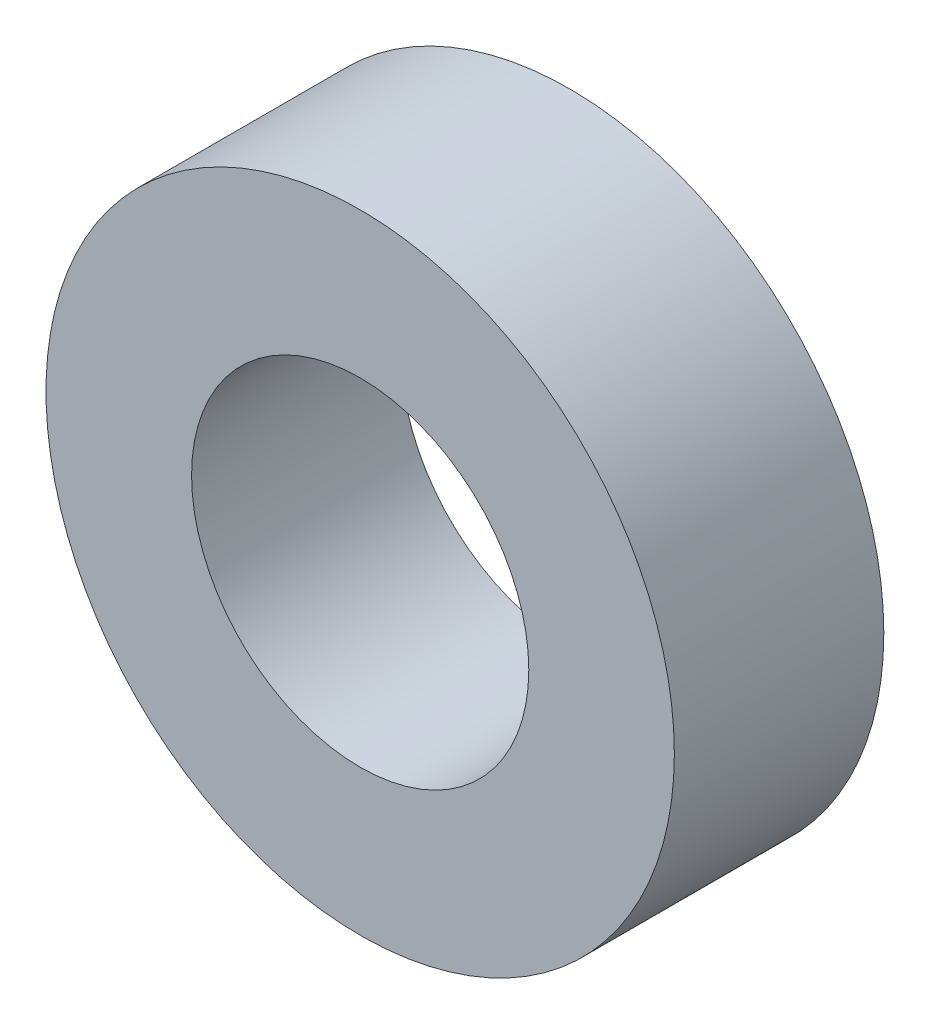
SolidWorks part; units mm, degrees
ref_plane "Front Plane" through (0, 0, 0) normal (0, 0, 1) x (1, 0, 0)
ref_plane "Top Plane" through (0, 0, 0) normal (0, 1, 0) x (1, 0, 0)
ref_plane "Right Plane" through (0, 0, 0) normal (1, 0, 0) x (0, 0, -1)
sketch "Sketch1" plane through (0, 0, 0) normal (0, 0, 1) x (1, 0, 0)
  circle A0 centre (0, 0) radius 1.61
  circle A1 centre (0, 0) radius 3
  dimension "D1" = 3.22
  dimension "D2" = 6
extrude "Boss-Extrude1" add sketch "Sketch1" along normal blind 2
